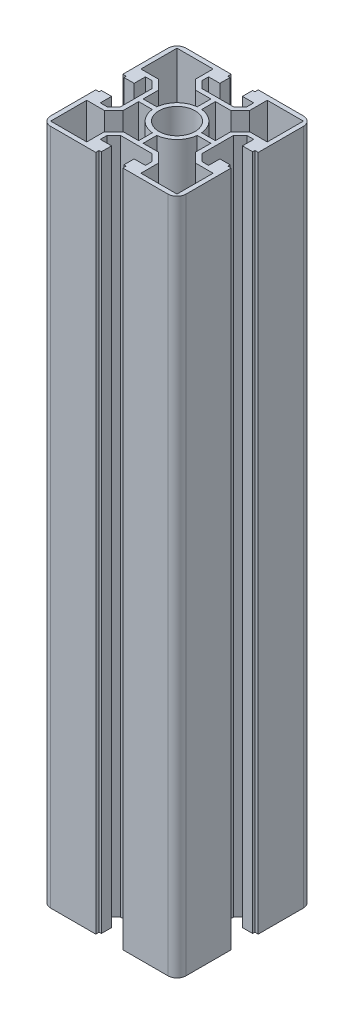
SolidWorks part; units mm, degrees
ref_plane "前视基准面" through (0, 0, 0) normal (0, 0, 1) x (1, 0, 0)
ref_plane "上视基准面" through (0, 0, 0) normal (0, 1, 0) x (1, 0, 0)
ref_plane "右视基准面" through (0, 0, 0) normal (1, 0, 0) x (0, 0, -1)
sketch "草图1" plane through (0, 0, 0) normal (0, 1, 0) x (1, 0, 0)
  line L0 (0, 32.6515) -> (0, -47.5) construction
  line L2 (-54.5455, 0) -> (57.7273, 0) construction
  line L82 (-16, 1) -> (-9.9499, 1)
  line L83 (-30, 6) -> (-28.5, 6)
  line L88 (-16, 1) -> (-16, 7.8284)
  line L89 (-16, 7.8284) -> (-20.1716, 12)
  line L90 (-20.1716, 12) -> (-28, 12)
  line L91 (-28, 12) -> (-28, 28)
  line L92 (-28, 28) -> (-12, 28)
  line L93 (-12, 28) -> (-12, 20.1716)
  line L94 (-12, 20.1716) -> (-7.8284, 16)
  line L95 (-7.8284, 16) -> (-1, 16)
  line L96 (-1, 16) -> (-1, 9.9499)
  line L97 (1, 9.9499) -> (1, 16)
  line L98 (1, 16) -> (7.8284, 16)
  line L99 (7.8284, 16) -> (12, 20.1716)
  line L100 (12, 20.1716) -> (12, 28)
  line L101 (12, 28) -> (28, 28)
  line L102 (28, 28) -> (28, 12)
  line L103 (28, 12) -> (20.1716, 12)
  line L104 (20.1716, 12) -> (16, 7.8284)
  line L105 (16, 7.8284) -> (16, 1)
  line L106 (16, 1) -> (9.9499, 1)
  line L107 (9.9499, -1) -> (16, -1)
  line L108 (16, -1) -> (16, -7.8284)
  line L109 (16, -7.8284) -> (20.1716, -12)
  line L110 (20.1716, -12) -> (28, -12)
  line L111 (28, -12) -> (28, -28)
  line L112 (28, -28) -> (12, -28)
  line L113 (12, -28) -> (12, -20.1716)
  line L114 (12, -20.1716) -> (7.8284, -16)
  line L115 (7.8284, -16) -> (1, -16)
  line L116 (1, -16) -> (1, -9.9499)
  line L117 (-1, -9.9499) -> (-1, -16)
  line L118 (-1, -16) -> (-7.8284, -16)
  line L119 (-7.8284, -16) -> (-12, -20.1716)
  line L120 (-12, -20.1716) -> (-12, -28)
  line L121 (-12, -28) -> (-28, -28)
  line L122 (-28, -28) -> (-28, -12)
  line L123 (-28, -12) -> (-20.1716, -12)
  line L124 (-20.1716, -12) -> (-16, -7.8284)
  line L125 (-16, -7.8284) -> (-16, -1)
  line L126 (-28.5, 6) -> (-28.5, 5)
  line L127 (-28.5, 5) -> (-24, 5)
  line L128 (-24, 5) -> (-24, 10)
  line L129 (-24, 10) -> (-21, 10)
  line L130 (-21, 10) -> (-18, 7)
  line L131 (-18, 7) -> (-18, -7)
  line L132 (-18, -7) -> (-21, -10)
  line L133 (-21, -10) -> (-24, -10)
  line L134 (-24, -10) -> (-24, -5)
  line L135 (-24, -5) -> (-28.5, -5)
  line L136 (-28.5, -5) -> (-28.5, -6)
  line L137 (-28.5, -6) -> (-30, -6)
  line L138 (-30, -6) -> (-30, -26)
  line L139 (-26, -30) -> (-6, -30)
  line L140 (-6, -30) -> (-6, -28.5)
  line L141 (-6, -28.5) -> (-5, -28.5)
  line L142 (-5, -28.5) -> (-5, -24)
  line L143 (-5, -24) -> (-10, -24)
  line L144 (-10, -24) -> (-10, -21)
  line L145 (-10, -21) -> (-7, -18)
  line L146 (-7, -18) -> (7, -18)
  line L147 (7, -18) -> (10, -21)
  line L148 (10, -21) -> (10, -24)
  line L149 (10, -24) -> (5, -24)
  line L150 (5, -24) -> (5, -28.5)
  line L151 (5, -28.5) -> (6, -28.5)
  line L152 (6, -28.5) -> (6, -30)
  line L153 (6, -30) -> (26, -30)
  line L154 (30, -26) -> (30, -6)
  line L155 (30, -6) -> (28.5, -6)
  line L156 (28.5, -6) -> (28.5, -5)
  line L157 (28.5, -5) -> (24, -5)
  line L158 (24, -5) -> (24, -10)
  line L159 (24, -10) -> (21, -10)
  line L160 (21, -10) -> (18, -7)
  line L161 (18, -7) -> (18, 7)
  line L162 (18, 7) -> (21, 10)
  line L163 (21, 10) -> (24, 10)
  line L164 (24, 10) -> (24, 5)
  line L165 (24, 5) -> (28.5, 5)
  line L166 (28.5, 5) -> (28.5, 6)
  line L167 (28.5, 6) -> (30, 6)
  line L168 (30, 6) -> (30, 26)
  line L169 (26, 30) -> (6, 30)
  line L170 (6, 30) -> (6, 28.5)
  line L171 (6, 28.5) -> (5, 28.5)
  line L172 (5, 28.5) -> (5, 24)
  line L173 (5, 24) -> (10, 24)
  line L174 (10, 24) -> (10, 21)
  line L175 (10, 21) -> (7, 18)
  line L176 (7, 18) -> (-7, 18)
  line L177 (-7, 18) -> (-10, 21)
  line L178 (-10, 21) -> (-10, 24)
  line L179 (-10, 24) -> (-5, 24)
  line L180 (-5, 24) -> (-5, 28.5)
  line L181 (-5, 28.5) -> (-6, 28.5)
  line L182 (-6, 28.5) -> (-6, 30)
  line L183 (-6, 30) -> (-26, 30)
  line L184 (-30, 26) -> (-30, 6)
  line L185 (-16, -1) -> (-9.9499, -1)
  arc A41 (-9.9499, -1) -> (-1, -9.9499) centre (0, 0) ccw
  circle A42 centre (0, 0) radius 8
  arc A43 (-26, -30) -> (-30, -26) centre (-26, -26) cw
  arc A44 (26, 30) -> (30, 26) centre (26, 26) cw
  arc A45 (-26, 30) -> (-30, 26) centre (-26, 26) ccw
  arc A46 (26, -30) -> (30, -26) centre (26, -26) ccw
  arc A47 (9.9499, 1) -> (1, 9.9499) centre (0, 0) ccw
  arc A48 (-1, 9.9499) -> (-9.9499, 1) centre (0, 0) ccw
  arc A49 (1, -9.9499) -> (9.9499, -1) centre (0, 0) ccw
extrude "凸台-拉伸1" add sketch "草图1" along normal blind 300
ref_plane "基准面1" through (0, 75, 0) normal (0, 1, 0) x (1, 0, 0)
